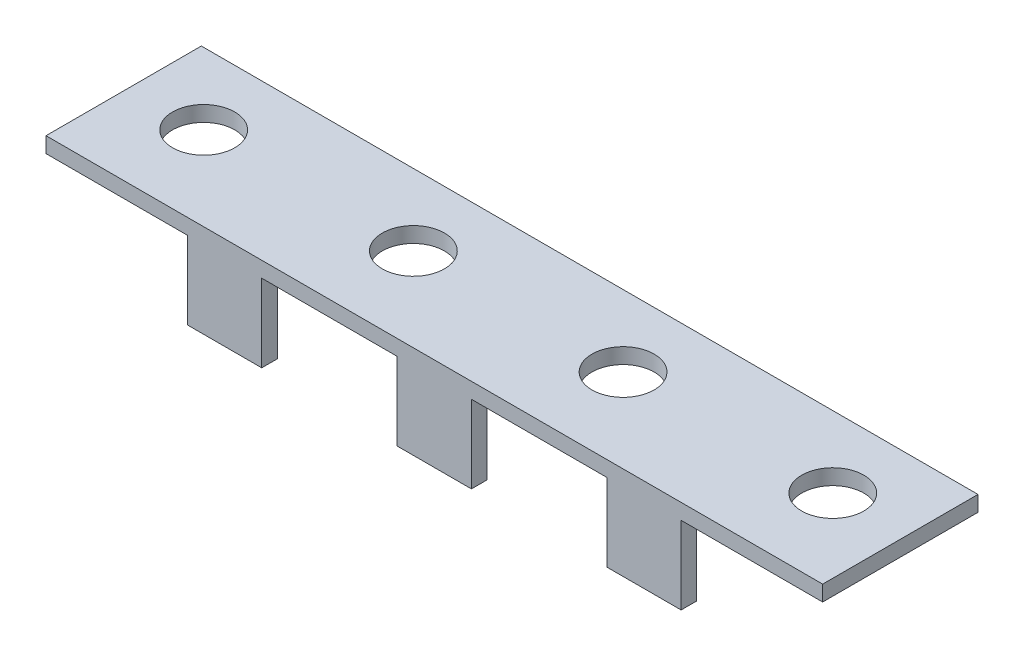
SolidWorks part; units mm, degrees
ref_plane "Front Plane" through (0, 0, 0) normal (0, 0, 1) x (1, 0, 0)
ref_plane "Top Plane" through (0, 0, 0) normal (0, 1, 0) x (1, 0, 0)
ref_plane "Right Plane" through (0, 0, 0) normal (1, 0, 0) x (0, 0, -1)
sketch "Sketch1" plane through (0, 0, 0) normal (0, 1, 0) x (1, 0, 0)
  line L0 (12.065, 13.716) -> (114.935, 13.716) construction
  line L1 (0, 0) -> (127, 0)
  line L2 (0, 0) -> (0, 25.4)
  line L3 (0, 25.4) -> (127, 25.4)
  line L4 (127, 0) -> (127, 25.4)
  line L5 (12.065, 13.716) -> (0, 13.716) construction
  line L6 (114.935, 13.716) -> (127, 13.716) construction
  circle A0 centre (12.065, 13.716) radius 5.08
  circle A1 centre (46.355, 13.716) radius 5.08
  circle A2 centre (80.645, 13.716) radius 5.08
  circle A3 centre (114.935, 13.716) radius 5.08
  dimension "D3" = 10.16
  dimension "D1" = 127
  dimension "D2" = 25.4
  dimension "D4" = 34.29
  dimension "D5" = 34.29
  dimension "D6" = 34.29
  dimension "D7" = 13.716
extrude "Boss-Extrude1" add sketch "Sketch1" along normal blind 2.54
sketch "Sketch2" plane through (0, 0, 0) normal (0, -1, 0) x (1, 0, 0)
  line L0 (127, 0) -> (127, -25.4) construction
  line L1 (0, 0) -> (127, 0)
  line L2 (0, 0) -> (0, -2.54)
  line L3 (0, -2.54) -> (127, -2.54)
  line L4 (127, 0) -> (127, -2.54)
  dimension "D1" = 2.54
extrude "Boss-Extrude2" add sketch "Sketch2" along normal blind 12.7
sketch "Sketch4" plane through (0, 0, -2.54) normal (0, 0, -1) x (-1, 0, 0)
  line L0 (-6.985, 2.54) -> (-17.145, 2.54) construction
  line L1 (-41.275, 2.54) -> (-51.435, 2.54) construction
  line L2 (-75.565, 2.54) -> (-85.725, 2.54) construction
  line L3 (-109.855, 2.54) -> (-120.015, 2.54) construction
  line L4 (-6.985, 2.54) -> (-17.145, 2.54) construction
  line L5 (-41.275, 2.54) -> (-51.435, 2.54) construction
  line L6 (-75.565, 2.54) -> (-85.725, 2.54) construction
  line L7 (-109.855, 2.54) -> (-120.015, 2.54) construction
  line L8 (0, -12.7) -> (-127, -12.7) construction
  line L9 (-127, 0) -> (-103.855, 0)
  line L10 (-127, 0) -> (-127, -12.7)
  line L11 (-127, -12.7) -> (-103.855, -12.7)
  line L12 (-103.855, 0) -> (-103.855, -12.7)
  line L13 (0, 0) -> (-127, 0) construction
  line L14 (-91.725, 0) -> (-69.565, 0)
  line L15 (-91.725, 0) -> (-91.725, -12.7)
  line L16 (-91.725, -12.7) -> (-69.565, -12.7)
  line L17 (-69.565, 0) -> (-69.565, -12.7)
  line L18 (-127, 0) -> (0, 0) construction
  line L19 (-57.435, 0) -> (-35.275, 0)
  line L20 (-57.435, 0) -> (-57.435, -12.7)
  line L21 (-57.435, -12.7) -> (-35.275, -12.7)
  line L22 (-35.275, 0) -> (-35.275, -12.7)
  line L23 (-23.145, 0) -> (0, 0)
  line L24 (-23.145, 0) -> (-23.145, -12.7)
  line L25 (-23.145, -12.7) -> (0, -12.7)
  line L26 (0, 0) -> (0, -12.7)
  line L27 (0, -12.7) -> (0, 0) construction
  dimension "D1" = 6
  dimension "D2" = 6
  dimension "D3" = 6
  dimension "D4" = 6
  dimension "D5" = 6
  dimension "D6" = 6
extrude "Cut-Extrude1" cut sketch "Sketch4" against normal up to surface (2.54 mm away) up to face at (63.5, -5.08, 0)
